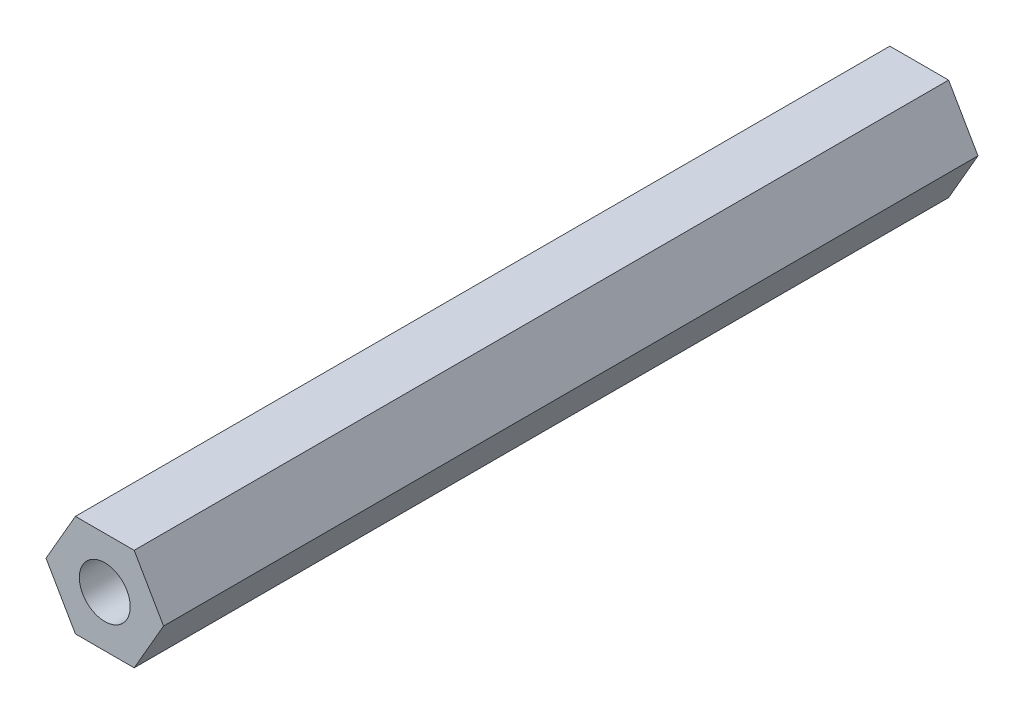
SolidWorks part; units mm, degrees
material "1060 Alloy"
ref_plane "Front Plane" through (0, 0, 0) normal (0, 0, 1) x (1, 0, 0)
ref_plane "Top Plane" through (0, 0, 0) normal (0, 1, 0) x (1, 0, 0)
ref_plane "Right Plane" through (0, 0, 0) normal (1, 0, 0) x (0, 0, -1)
sketch "Sketch1" plane through (0, 0, 0) normal (0, 0, 1) x (1, 0, 0)
  line L1 (3.6662, 6.35) -> (-3.6662, 6.35)
  line L2 (-3.6662, 6.35) -> (-7.3323, 0)
  line L3 (-7.3323, 0) -> (-3.6662, -6.35)
  line L4 (-3.6662, -6.35) -> (3.6662, -6.35)
  line L5 (3.6662, -6.35) -> (7.3323, 0)
  line L6 (7.3323, 0) -> (3.6662, 6.35)
  circle A0 centre (0, 0) radius 6.35 construction
  circle A1 centre (0, 0) radius 3.175
  dimension "D2" = 6.35
  dimension "D1" = 12.7
extrude "Boss-Extrude1" add sketch "Sketch1" along normal blind 101.6
